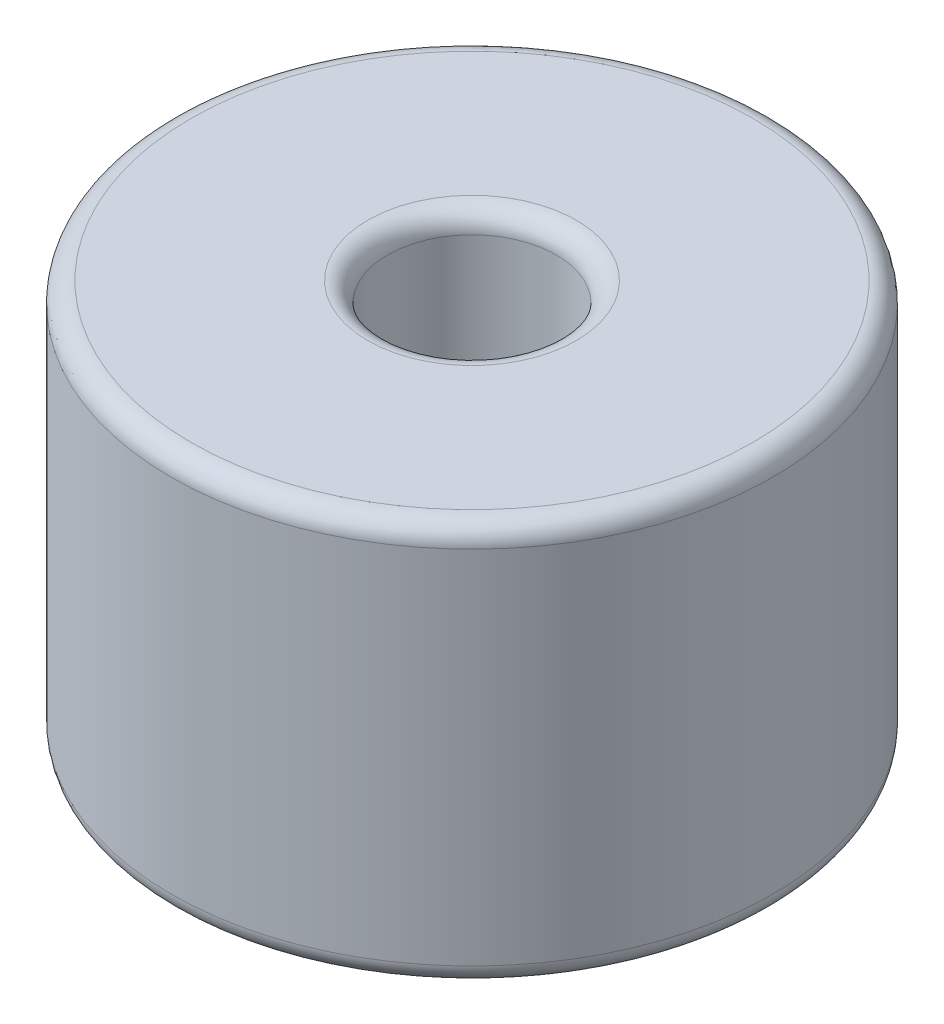
SolidWorks part; units mm, degrees
ref_plane "Front Plane" through (0, 0, 0) normal (0, 0, 1) x (1, 0, 0)
ref_plane "Top Plane" through (0, 0, 0) normal (0, 1, 0) x (1, 0, 0)
ref_plane "Right Plane" through (0, 0, 0) normal (1, 0, 0) x (0, 0, -1)
sketch "Sketch1" plane through (0, 0, 0) normal (0, 1, 0) x (1, 0, 0)
  circle A0 centre (0, 0) radius 2.1
  circle A1 centre (0, 0) radius 7.5
  dimension "D1" = 4.2
  dimension "D2" = 15
extrude "Boss-Extrude1" add sketch "Sketch1" along normal blind 10
fillet "Fillet1" radius 0.5 4 edges at (0, 0, 2.1) (0, 10, 2.1) (0, 0, 7.5) (0, 10, 7.5)
